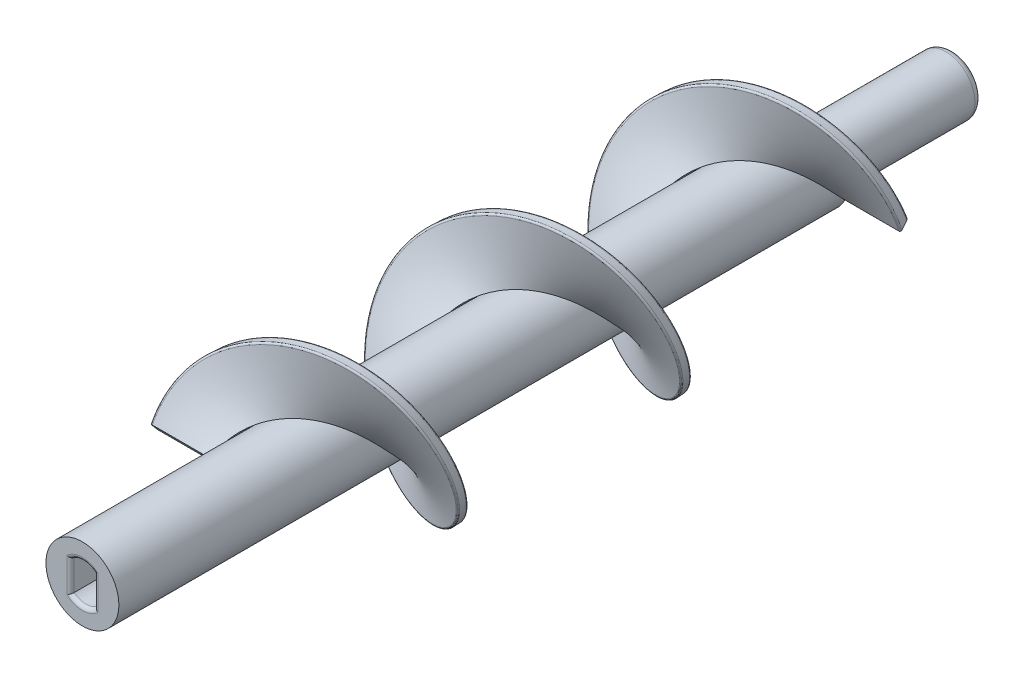
SolidWorks part; units mm, degrees
ref_plane "Front Plane" through (0, 0, 0) normal (0, 0, 1) x (1, 0, 0)
ref_plane "Top Plane" through (0, 0, 0) normal (0, 1, 0) x (1, 0, 0)
ref_plane "Right Plane" through (0, 0, 0) normal (1, 0, 0) x (0, 0, -1)
sketch "Sketch2" plane through (0, 0, 0) normal (0, 0, 1) x (1, 0, 0)
  circle A0 centre (0, 0) radius 4.9
  dimension "D1" = 9.8
extrude "Boss-Extrude1" add sketch "Sketch2" along normal mid plane 98
sketch "Sketch3" plane through (0, 0, -49) normal (0, 0, -1) x (-1, 0, 0)
  circle A0 centre (0, 0) radius 4
curve "Helix/Spiral1" pitch 30 height 75 turns 2.5
ref_plane "Plane1" through (4, 0, -49) normal (0, 0.6422, 0.7666) x (1, 0, 0)
sketch "Sketch5" plane through (4, 0, -49) normal (0, 0.6422, 0.7666) x (1, 0, 0)
  line L1 (0.9, 0) -> (8.65, 0)
  line L2 (0.9, 0) -> (0.9, -1.5)
  line L3 (0.9, -1.5) -> (8.65, -1.5)
  line L4 (8.9, -0.25) -> (8.9, -1.25)
  arc A0 (8.65, -1.5) -> (8.9, -1.25) centre (8.65, -1.25) ccw
  arc A1 (8.65, 0) -> (8.9, -0.25) centre (8.65, -0.25) cw
  ellipse E0 centre (-4, 0) end of major axis (-8.9, 0) minor radius 3.7561 construction
  point P14 (8.9, 0)
  dimension "D3" = 0.25
  dimension "D1" = 8
  dimension "D2" = 1.5
sweep "Sweep1" add profiles "Sketch5" path "Helix/Spiral1"
sketch "Sketch6" plane through (0, 0, 49) normal (0, 0, 1) x (1, 0, 0)
  line L1 (-1.6, -2.0494) -> (1.6, -2.0494)
  line L2 (-1.6, -2.0494) -> (-1.6, 2.0494)
  line L3 (-1.6, 2.0494) -> (1.6, 2.0494)
  line L4 (1.6, -2.0494) -> (1.6, 2.0494)
  line L5 (-1.6, -2.0494) -> (1.6, 2.0494) construction
  line L6 (-1.6, 2.0494) -> (1.6, -2.0494) construction
  circle A0 centre (0, 0) radius 2.6
  dimension "D1" = 5.2
  dimension "D2" = 3.2
extrude "Cut-Extrude1" cut sketch "Sketch6" against normal blind 9 contours L3 A0 | L1 L4 L3 L2 | L1 A0
sketch "Sketch7" plane through (0, 0, -49) normal (0, 0, -1) x (-1, 0, 0)
  circle A0 centre (0, 0) radius 3.9
  dimension "D1" = 7.8
extrude "Boss-Extrude3" add sketch "Sketch7" along normal blind 19
fillet "Fillet1" radius 1 1 edges at (-3.9, 0, -68)
fillet "Fillet2" radius 0.5 4 edges at (0, 2.6, 49) (0, -2.6, 49) (1.6, 0, 49) (-1.6, 0, 49)
